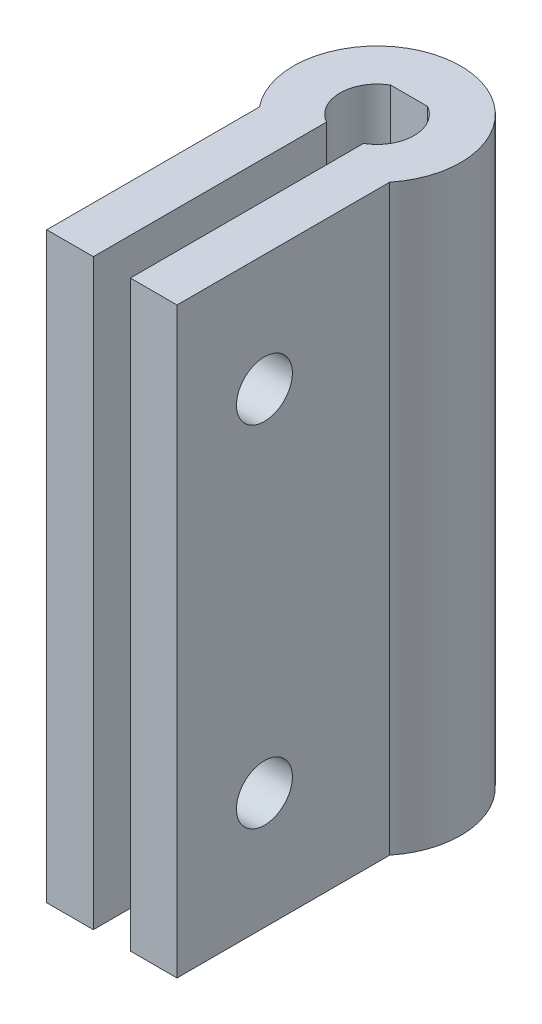
SolidWorks part; units mm, degrees
ref_plane "Front Plane" through (0, 0, 0) normal (0, 0, 1) x (1, 0, 0)
ref_plane "Top Plane" through (0, 0, 0) normal (0, 1, 0) x (1, 0, 0)
ref_plane "Right Plane" through (0, 0, 0) normal (1, 0, 0) x (0, 0, -1)
sketch "Sketch1" plane through (0, 0, 0) normal (0, 1, 0) x (1, 0, 0)
  line L0 (-1.5875, -2.7496) -> (-1.5875, -22.7496)
  line L1 (1.5875, -2.7496) -> (1.5875, -22.7496)
  line L2 (1.5875, 2.7496) -> (-1.5875, 2.7496)
  line L3 (5.5875, -4.5012) -> (5.5875, -22.7496)
  line L4 (-5.5875, -4.5012) -> (-5.5875, -22.7496)
  line L5 (-5.5875, -22.7496) -> (-1.5875, -22.7496)
  line L6 (1.5875, -22.7496) -> (5.5875, -22.7496)
  arc A0 (1.5875, -2.7496) -> (1.5875, 2.7496) centre (0, 0) ccw
  arc A1 (5.5875, -4.5012) -> (-5.5875, -4.5012) centre (0, 0) ccw
  arc A2 (-1.5875, 2.7496) -> (-1.5875, -2.7496) centre (0, 0) ccw
  arc A4 (1.5875, -2.7496) -> (-1.5875, -2.7496) centre (0, 0) ccw construction
  point P13 (9.525, 0)
  point P14 (7.4275, -5.963)
  point P15 (0, 0)
  point P16 (-9.525, 0)
  point P17 (-9.525, 0)
  point P18 (0, 0)
  point P19 (-14.525, 0)
  point P20 (0, 0)
  point P21 (-8.1894, -4.8641)
  point P22 (-7.3738, -5.963)
  dimension "D1" = 3.175
  dimension "D2" = 20
  dimension "D3" = 3.175
  dimension "D5" = 3.175
  dimension "D4" = 4
extrude "Boss-Extrude1" add sketch "Sketch1" along normal blind 50
hole_wizard "M4 Clearance Hole1" positions "Sketch2" profile "Sketch3" hole size "M4" standard "ANSI Metric" end condition through all
sketch "Sketch2" plane through (5.5875, 0, 0) normal (1, 0, 0) x (0, 0, -1)
  line L2 (-22.7496, 50) -> (-22.7496, 0) construction
  line L3 (-22.7496, 0) -> (-4.5012, 0) construction
  line L4 (-22.7496, 50) -> (-4.5012, 50) construction
  point P0 (-15.2496, 40)
  point P4 (-15.2496, 10)
  dimension "D1" = 10
  dimension "D2" = 10
  dimension "D3" = 7.5
sketch "Sketch3" plane through (5.5875, 40, 15.2496) normal (0, 1, 0) x (0, 0, -1)
  line L0 (0, 0) -> (0, 12.7625)
  line L1 (0, 12.7625) -> (2.4, 12.7625)
  line L2 (2.4, 12.7625) -> (2.4, 0)
  line L5 (2.4, 0) -> (0, 0)
  line L11 (0, -6.35) -> (0, 107.95) construction
  dimension "Thru Hole Dia." = 4.8
  dimension "Thru Hole Depth" = 12.7625
